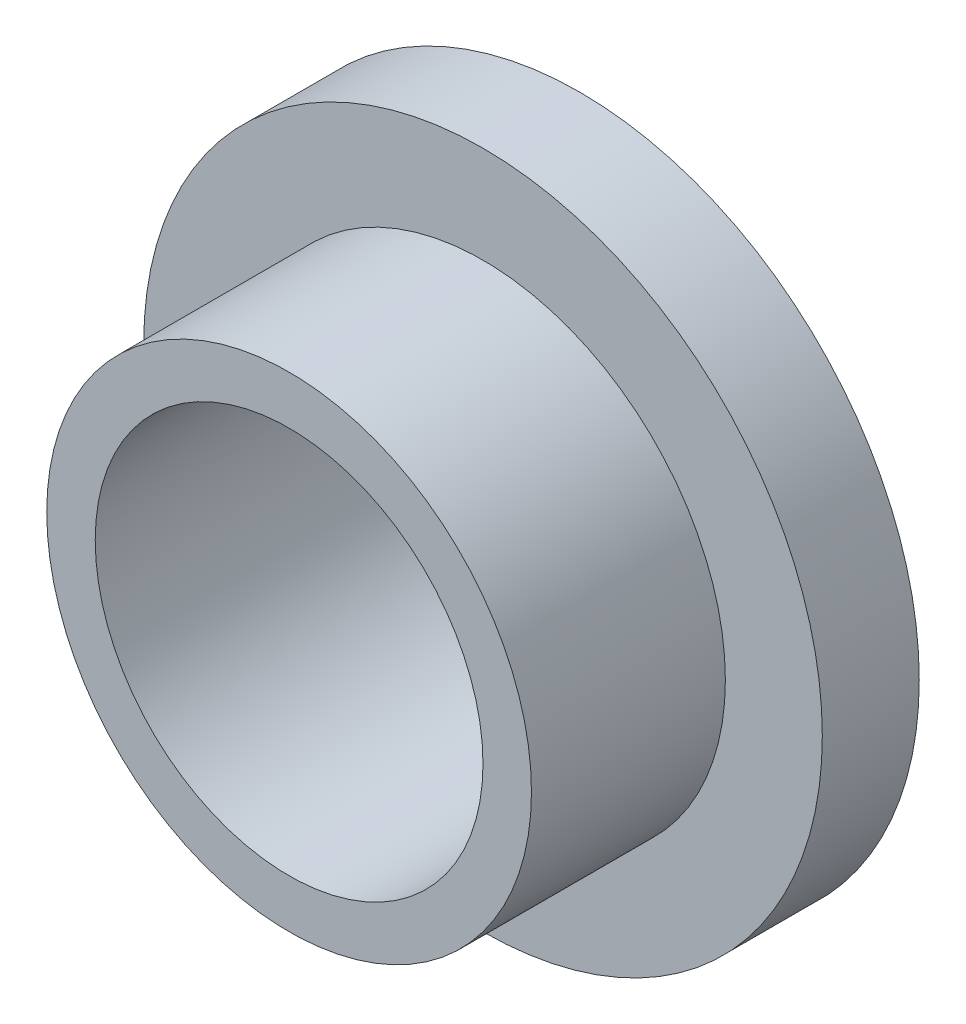
SolidWorks part; units mm, degrees
material "Brass"
ref_plane "Front Plane" through (0, 0, 0) normal (0, 0, 1) x (1, 0, 0)
ref_plane "Top Plane" through (0, 0, 0) normal (0, 1, 0) x (1, 0, 0)
ref_plane "Right Plane" through (0, 0, 0) normal (1, 0, 0) x (0, 0, -1)
sketch "base" plane through (0, 0, 0) normal (1, 0, 0) x (0, 0, -1)
  line L0 (0, 0) -> (0, 6.35) construction
  line L1 (-4.7625, 7.9375) -> (4.7625, 7.9375)
  line L2 (-4.7625, 7.9375) -> (-4.7625, 6.35)
  line L3 (-4.7625, 6.35) -> (4.7625, 6.35)
  line L4 (4.7625, 7.9375) -> (4.7625, 6.35)
  line L5 (-5.8805, 0) -> (7.0751, 0) construction
  dimension "width" = 9.525
  dimension "ID" = 12.7
  dimension "OD" = 15.875
revolve "RevolveBase" add sketch "base" angle 360 about L5
sketch "flange" plane through (0, 0, 0) normal (1, 0, 0) x (0, 0, -1)
  line L0 (-11.055, 0) -> (14.5901, 0) construction
  line L1 (4.7625, 7.9375) -> (1.5875, 7.9375)
  line L2 (4.7625, 7.9375) -> (4.7625, 11.1125)
  line L3 (4.7625, 11.1125) -> (1.5875, 11.1125)
  line L4 (1.5875, 7.9375) -> (1.5875, 11.1125)
  dimension "width" = 3.175
  dimension "OD" = 22.225
revolve "RevolveFlange" add sketch "flange" angle 360 about L0
sketch "Sketch3" plane through (0, 0, -4.7625) normal (0, 0, -1) x (-1, 0, 0)
  line L1 (3.6662, 6.35) -> (-3.6662, 6.35)
  line L2 (-3.6662, 6.35) -> (-7.3323, 0)
  line L3 (-7.3323, 0) -> (-3.6662, -6.35)
  line L4 (-3.6662, -6.35) -> (3.6662, -6.35)
  line L5 (3.6662, -6.35) -> (7.3323, 0)
  line L6 (7.3323, 0) -> (3.6662, 6.35)
  circle A0 centre (0, 0) radius 6.35 construction
  circle A1 centre (0, 0) radius 6.35 construction
extrude "Cut-ExtrudeHex" [suppressed] cut sketch "Sketch3" against normal through all
